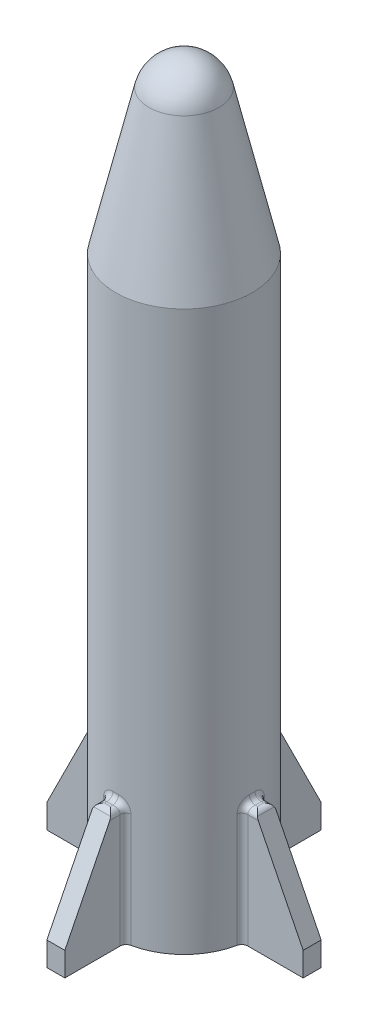
SolidWorks part; units mm, degrees
ref_plane "Front Plane" through (0, 0, 0) normal (0, 0, 1) x (1, 0, 0)
ref_plane "Top Plane" through (0, 0, 0) normal (0, 1, 0) x (1, 0, 0)
ref_plane "Right Plane" through (0, 0, 0) normal (1, 0, 0) x (0, 0, -1)
sketch "Sketch2" plane through (0, 0, 0) normal (0, 0, 1) x (1, 0, 0)
  line L0 (0, 46.6764) -> (-2.7773, 58.6764)
  line L3 (-5.7, 0) -> (0, 0)
  line L4 (0, 46.6764) -> (0, 0)
  line L8 (-5.7, 58) -> (-5.7, 0)
  line L9 (-5.7, 61) -> (-5.7, 58)
  line L11 (0, -55) -> (0, 55) construction
  arc A0 (-2.7773, 58.6764) -> (-5.7, 61) centre (-5.7, 58) ccw
  point P0 (0, 0)
  dimension "D1" = 5.7
  dimension "D2" = 3
  dimension "D3" = 12
  dimension "D4" = 61
revolve "Revolve1" add sketch "Sketch2" angle 360 about L8
shell "Shell1" thickness 1
sketch "Sketch4" plane through (0, 0, 0) normal (1, 0, 0) x (0, 0, -1)
  line L0 (-0.75, 0) -> (0.75, 0)
  line L2 (0.75, 0) -> (0.75, 10)
  line L3 (0.75, 10) -> (-0.75, 10)
  line L4 (-0.75, 0) -> (-0.75, 10)
  line L5 (6.16, 0) -> (-6.16, 0) construction
  line L6 (0, 6.16) -> (0, -6.16) construction
  point P0 (0, 0)
  point P8 (0, 0)
  dimension "D1" = 1.5
  dimension "D2" = 10
extrude "Boss-Extrude2" add sketch "Sketch4" against normal up to surface (5.0496 mm away) from offset 5
sketch "Sketch5" plane through (0, 0, 0.75) normal (0, 0, 1) x (1, 0, 0)
  line L0 (1, 10) -> (5, 2)
  line L1 (-0.0496, 10) -> (5, 10) construction
  line L2 (5, 10) -> (5, 0) construction
  line L3 (1, 10) -> (5, 10)
  line L4 (5, 10) -> (5, 2)
  dimension "D1" = 4
  dimension "D2" = 8
extrude "Cut-Extrude1" cut sketch "Sketch5" against normal blind 1.5
pattern_circular "CirPattern1" count 4 over 360 about axis through (-5.7, 0, 0) along (0, 1, 0) of "Boss-Extrude2", "Cut-Extrude1"
fillet "Fillet1" radius 0.5 24 edges at (-6.45, 5, 5.6504) (-4.95, 5, -5.6504) (-5.7, 10, 5.7) (-0.0496, 5, 0.75) (-5.7, 10, -5.7) (-11.3504, 5, 0.75) (-11.3504, 5, -0.75) (-6.45, 10, 6.1752) (-5.7, 10, 6.7) (-4.95, 10, 6.1752) (-4.95, 5, 5.6504) (0.4752, 10, 0.75) (0.4752, 10, -0.75) (1, 10, 0) (0, 10, 0) (-0.0496, 5, -0.75) (-4.95, 10, -6.1752) (-6.45, 10, -6.1752) (-5.7, 10, -6.7) (-6.45, 5, -5.6504) (-11.4, 10, 0) (-11.8752, 10, -0.75) (-11.8752, 10, 0.75) (-12.4, 10, 0)
